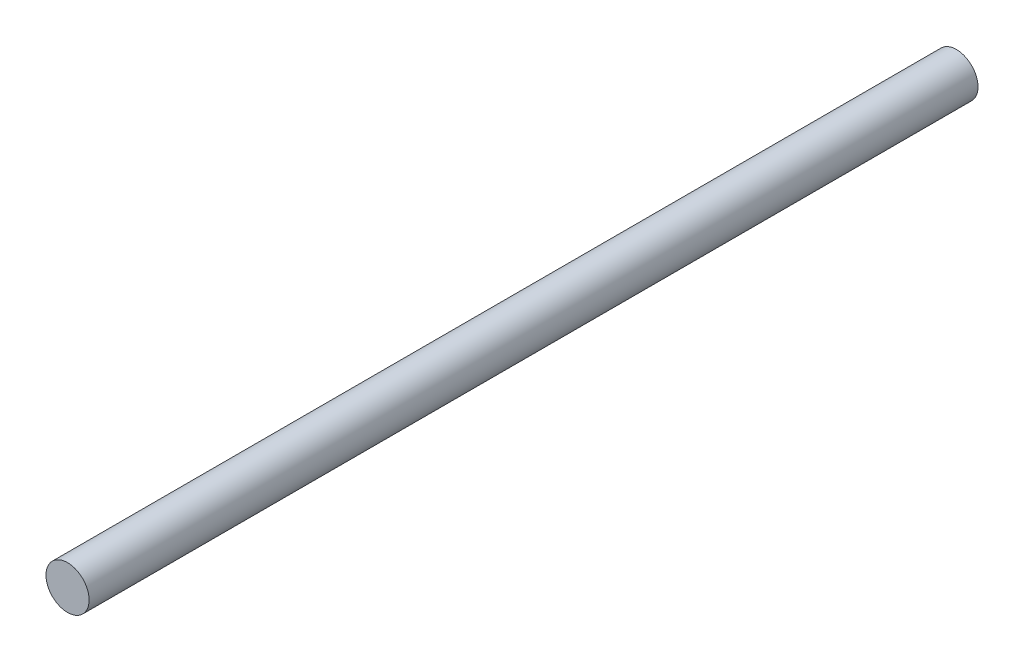
SolidWorks part; units mm, degrees
ref_plane "Front Plane" through (0, 0, 0) normal (0, 0, 1) x (1, 0, 0)
ref_plane "Top Plane" through (0, 0, 0) normal (0, 1, 0) x (1, 0, 0)
ref_plane "Right Plane" through (0, 0, 0) normal (1, 0, 0) x (0, 0, -1)
sketch "Sketch1" plane through (0, 0, 0) normal (0, 0, 1) x (1, 0, 0)
  circle A0 centre (0, 0) radius 1.5
  dimension "D1" = 3
extrude "Boss-Extrude1" add sketch "Sketch1" along normal blind 61.77
